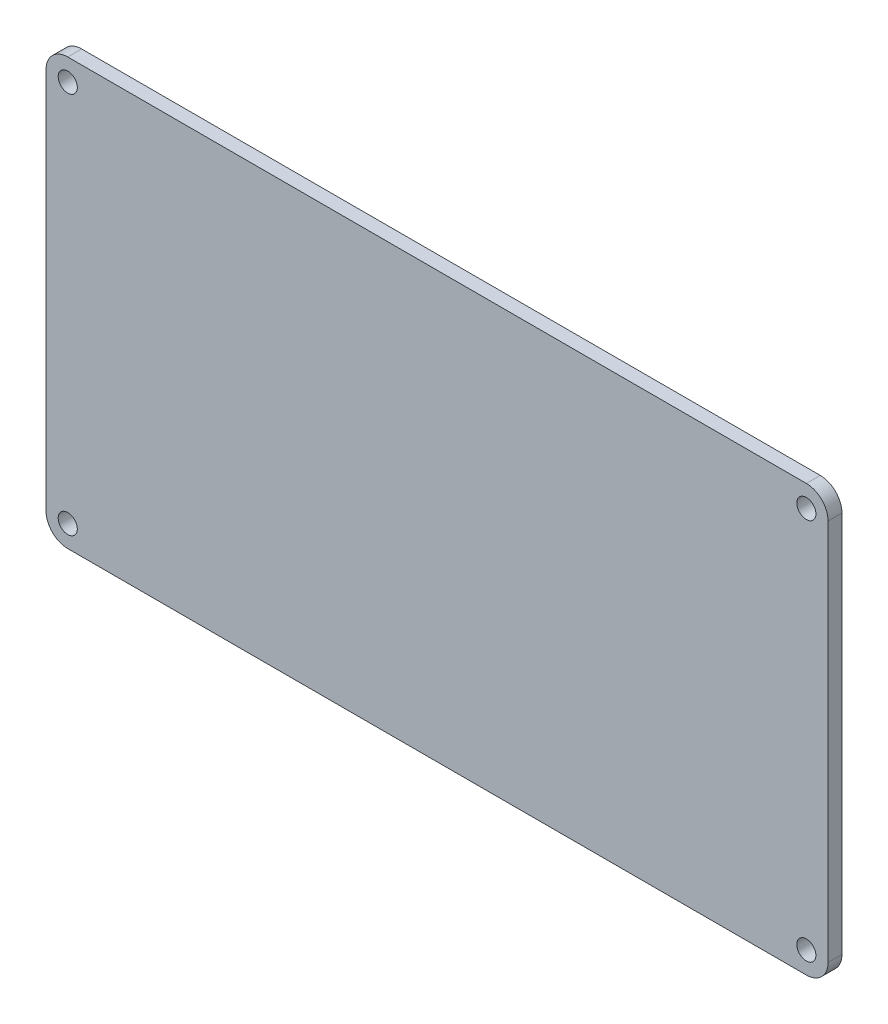
SolidWorks part; units mm, degrees
ref_plane "前视基准面" through (0, 0, 0) normal (0, 0, 1) x (1, 0, 0)
ref_plane "上视基准面" through (0, 0, 0) normal (0, 1, 0) x (1, 0, 0)
ref_plane "右视基准面" through (0, 0, 0) normal (1, 0, 0) x (0, 0, -1)
sketch "草图1" plane through (0, 0, 0) normal (0, 0, 1) x (1, 0, 0)
  line L1 (-45, 24.5) -> (45, 24.5)
  line L2 (-45, 24.5) -> (-45, -24.5)
  line L3 (-45, -24.5) -> (45, -24.5)
  line L4 (45, 24.5) -> (45, -24.5)
  line L5 (-45, 24.5) -> (45, -24.5) construction
  line L6 (-45, -24.5) -> (45, 24.5) construction
  point P0 (0, 0)
  dimension "D1" = 49
  dimension "D2" = 90
extrude "凸台-拉伸1" add sketch "草图1" along normal blind 1.6
fillet "圆角1" radius 2.5 4 edges at (-45, 24.5, 0.8) (-45, -24.5, 0.8) (45, -24.5, 0.8) (45, 24.5, 0.8)
sketch "草图2" plane through (0, 0, 0) normal (0, 0, -1) x (-1, 0, 0)
  circle A0 centre (-42.5, -22) radius 1.1
  circle A1 centre (-42.5, 22) radius 1.1
  circle A2 centre (42.5, 22) radius 1.1
  circle A3 centre (42.5, -22) radius 1.1
  dimension "D1" = 2.2
  dimension "D2" = 2.2
  dimension "D3" = 2.2
  dimension "D4" = 2.2
extrude "切除-拉伸1" cut sketch "草图2" against normal blind 26.6
